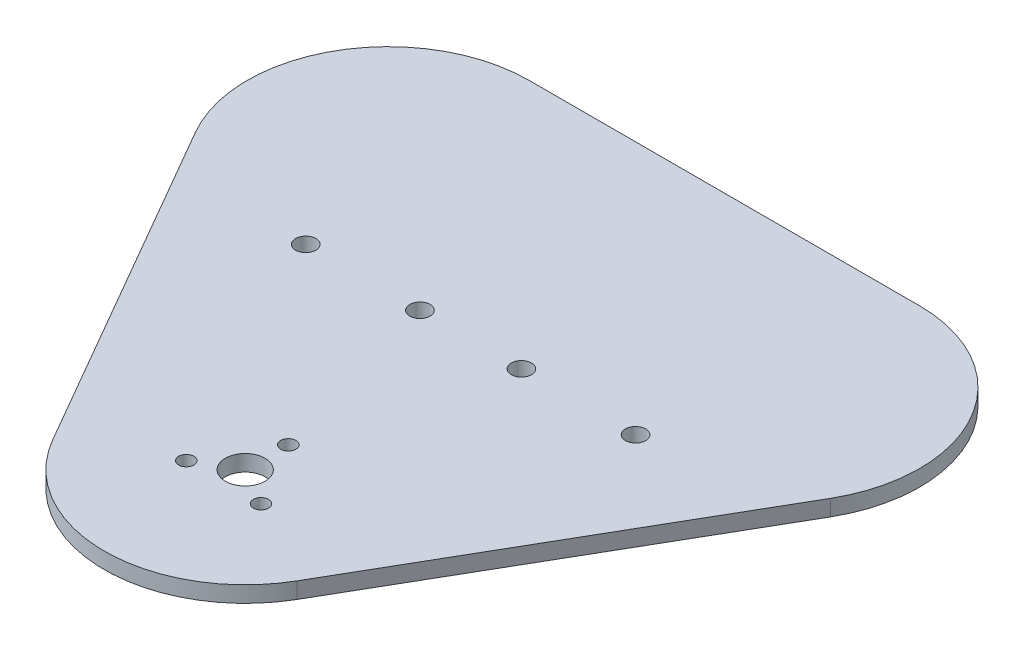
SolidWorks part; units mm, degrees
ref_plane "Front Plane" through (0, 0, 0) normal (0, 0, 1) x (1, 0, 0)
ref_plane "Top Plane" through (0, 0, 0) normal (0, 1, 0) x (1, 0, 0)
ref_plane "Right Plane" through (0, 0, 0) normal (1, 0, 0) x (0, 0, -1)
sketch "Sketch1" plane through (0, 0, 0) normal (0, 1, 0) x (1, 0, 0)
  line L0 (0, -94.9451) -> (-86.6025, 55.0549)
  line L1 (-86.6025, 55.0549) -> (86.6025, 55.0549)
  line L2 (86.6025, 55.0549) -> (0, -94.9451)
  point P2 (0, 55.0549)
  dimension "D1" = 150
extrude "Boss-Extrude1" add sketch "Sketch1" along normal blind 3.175
fillet "Fillet1" radius 27.78 3 edges at (86.6025, 1.5875, -55.0549) (-86.6025, 1.5875, -55.0549) (0, 1.5875, 94.9451)
sketch "Sketch2" plane through (0, 3.175, 0) normal (0, 1, 0) x (1, 0, 0)
  circle A0 centre (0, -39.3851) radius 20.9
  arc A2 (-24.0582, -53.2751) -> (24.0582, -53.2751) centre (0, -39.3851) ccw construction
  dimension "D1" = 41.8
sketch "Sketch5" plane through (0, 3.175, 0) normal (0, 1, 0) x (1, 0, 0)
  line L0 (32.5, 5.0549) -> (-32.5, 5.0549) construction
  line L1 (-10, 5.0549) -> (10, 5.0549) construction
  line L2 (38.4862, 55.0549) -> (-38.4862, 55.0549) construction
  circle A0 centre (32.5, 5.0549) radius 2
  circle A1 centre (-32.5, 5.0549) radius 2
  circle A4 centre (-10, 5.0549) radius 2
  circle A5 centre (10, 5.0549) radius 2
  point P4 (0, 5.0549)
  point P13 (0, 5.0549)
  dimension "D2" = 4
  dimension "D1" = 50
  dimension "D3" = 65
  dimension "D4" = 20
extrude "Cut-Extrude2" cut sketch "Sketch5" against normal through all
sketch "Sketch7" plane through (0, 3.175, 0) normal (0, 1, 0) x (1, 0, 0)
  line L0 (-7.3612, -43.6351) -> (0, -30.8851) construction
  line L1 (0, -30.8851) -> (7.3612, -43.6351) construction
  line L2 (7.3612, -43.6351) -> (-7.3612, -43.6351) construction
  line L3 (-7.3612, -43.6351) -> (3.6806, -37.2601) construction
  line L4 (-3.6806, -37.2601) -> (7.3612, -43.6351) construction
  circle A0 centre (0, -30.8851) radius 1.5
  circle A1 centre (-7.3612, -43.6351) radius 1.5
  circle A2 centre (7.3612, -43.6351) radius 1.5
  circle A3 centre (0, -39.3851) radius 10
  circle A5 centre (0, -39.3851) radius 3.925
  point P9 (0, -39.3851)
  dimension "D1" = 3
  dimension "D2" = 20
  dimension "D3" = 7.85
extrude "Cut-Extrude3" cut sketch "Sketch7" against normal blind 10 contours A0 | A1 | A5 | A2
